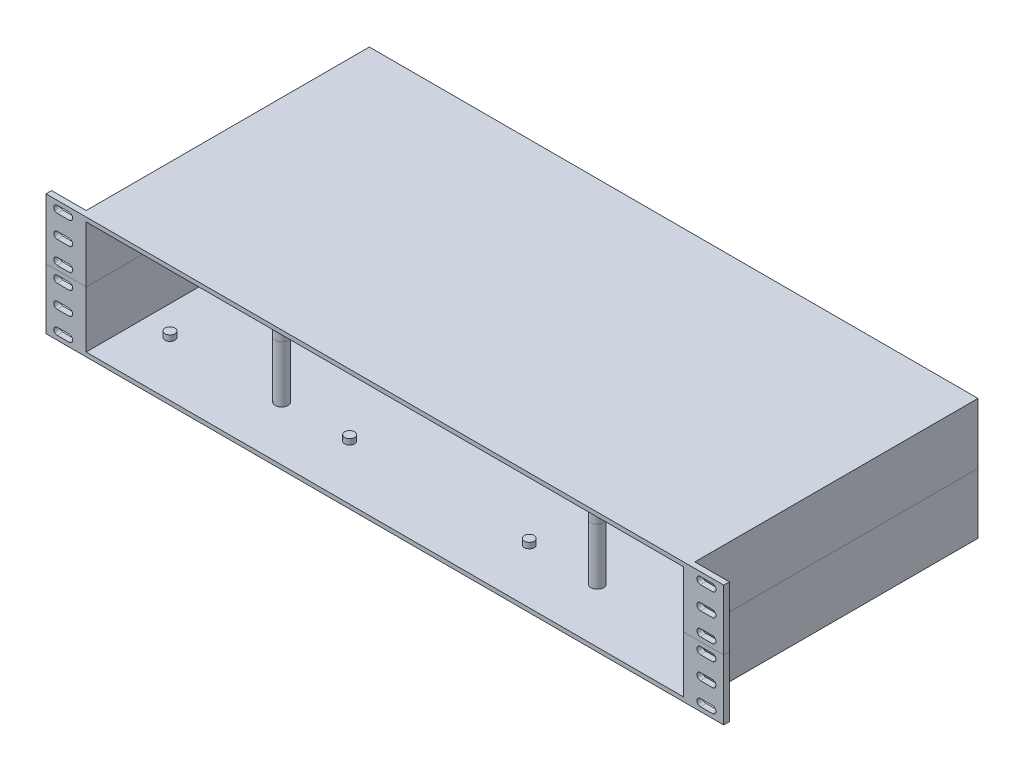
SolidWorks part; units mm, degrees
ref_plane "Front Plane" through (0, 0, 0) normal (0, 0, 1) x (1, 0, 0)
ref_plane "Top Plane" through (0, 0, 0) normal (0, 1, 0) x (1, 0, 0)
ref_plane "Right Plane" through (0, 0, 0) normal (1, 0, 0) x (0, 0, -1)
sketch "Sketch1" plane through (0, 0, 0) normal (0, 1, 0) x (1, 0, 0)
  line L0 (-15.8852, 0) -> (-227.8852, 0) construction
  line L1 (212, -98.3) -> (-212, -98.3)
  line L2 (212, -98.3) -> (212, 98.3)
  line L3 (212, 98.3) -> (-212, 98.3)
  line L4 (-212, -98.3) -> (-212, 98.3)
  line L5 (212, -98.3) -> (-212, 98.3) construction
  line L6 (212, 98.3) -> (-212, -98.3) construction
  line L7 (216, -102.5) -> (-216, -102.5)
  line L8 (216, -102.5) -> (216, 102.5)
  line L9 (216, 102.5) -> (-216, 102.5)
  line L10 (-216, -102.5) -> (-216, 102.5)
  line L11 (216, -102.5) -> (-216, 102.5) construction
  line L12 (216, 102.5) -> (-216, -102.5) construction
  line L13 (0, -98.3) -> (0, 98.3) construction
  point P0 (0, 0)
  point P6 (0, 0)
  point P14 (63.75, 63.75)
  point P16 (112, 63.75)
  point P17 (191.25, 63.75)
  dimension "D1" = 432
  dimension "D2" = 424
  dimension "D3" = 205
  dimension "D4" = 196.6
  dimension "D5" = 63.75
  dimension "D6" = 382.5
  dimension "D7" = 127.5
  dimension "D8" = 224
sketch "Sketch2" plane through (0, 0, 0) normal (0, 1, 0) x (1, 0, 0)
  line L0 (216, 102.5) -> (-216, 102.5) construction
  line L1 (216, -102.5) -> (216, 102.5) construction
  line L2 (216, -102.5) -> (-216, -102.5) construction
  line L3 (-216, -102.5) -> (-216, 102.5) construction
  line L4 (216, 102.5) -> (-216, 102.5)
  line L5 (216, -102.5) -> (216, 102.5)
  line L6 (216, -102.5) -> (-216, -102.5)
  line L7 (-216, -102.5) -> (-216, 102.5)
extrude "Boss-Extrude1" add sketch "Sketch2" along normal blind 3
sketch "Sketch3" plane through (0, 3, 0) normal (0, 1, 0) x (1, 0, 0)
  line L0 (216, -102.5) -> (-216, -102.5) construction
  line L1 (-212, -98.3) -> (-212, 98.3) construction
  line L2 (212, 98.3) -> (-212, 98.3) construction
  line L3 (212, -98.3) -> (212, 98.3) construction
  line L4 (216, -102.5) -> (216, 102.5) construction
  line L5 (216, 102.5) -> (-216, 102.5) construction
  line L6 (-216, -102.5) -> (-216, 102.5) construction
  line L7 (216, -102.5) -> (212, -102.5)
  line L8 (-212, -102.5) -> (-212, 98.3)
  line L9 (212, 98.3) -> (-212, 98.3)
  line L10 (212, -102.5) -> (212, 98.3)
  line L11 (216, -102.5) -> (216, 102.5)
  line L12 (216, 102.5) -> (-216, 102.5)
  line L13 (-216, -102.5) -> (-216, 102.5)
  line L14 (-212, -102.5) -> (-216, -102.5)
extrude "Boss-Extrude2" add sketch "Sketch3" along normal blind 40
sketch "Sketch4" plane through (0, 3, 0) normal (0, 1, 0) x (1, 0, 0)
  circle A0 centre (63.75, 63.75) radius 3.5
  circle A1 centre (191.25, 63.75) radius 3.5
  dimension "D1" = 7
extrude "Boss-Extrude3" add sketch "Sketch4" along normal blind 4
sketch "Sketch5" plane through (0, 3, 0) normal (0, 1, 0) x (1, 0, 0)
  circle A0 centre (112, 63.75) radius 4.5
  dimension "D1" = 9
extrude "Boss-Extrude4" add sketch "Sketch5" along normal blind 40
sketch "Sketch6" plane through (0, 0, 102.5) normal (0, 0, 1) x (1, 0, 0)
  line L0 (-216, 0) -> (216, 0) construction
  line L1 (216, 43) -> (240.5, 43)
  line L2 (216, 43) -> (216, 0)
  line L3 (216, 0) -> (240.5, 0)
  line L4 (240.5, 43) -> (240.5, 0)
  line L5 (0, 0) -> (0, 43) construction
  line L6 (-212, 43) -> (212, 43) construction
  line L7 (216, 21.5) -> (240.5, 21.5) construction
  line L8 (224, 21.5) -> (232.5, 21.5) construction
  line L9 (224, 24) -> (232.5, 24)
  line L10 (224, 19) -> (232.5, 19)
  line L11 (228.25, 43) -> (228.25, 21.5) construction
  line L12 (224, 37.5) -> (232.5, 37.5) construction
  line L13 (224, 40) -> (232.5, 40)
  line L14 (224, 35) -> (232.5, 35)
  line L15 (224, 5.5) -> (232.5, 5.5) construction
  line L16 (224, 8) -> (232.5, 8)
  line L17 (224, 3) -> (232.5, 3)
  arc A0 (224, 24) -> (224, 19) centre (224, 21.5) ccw
  arc A1 (232.5, 19) -> (232.5, 24) centre (232.5, 21.5) ccw
  arc A2 (224, 40) -> (224, 35) centre (224, 37.5) ccw
  arc A3 (232.5, 35) -> (232.5, 40) centre (232.5, 37.5) ccw
  arc A4 (224, 8) -> (224, 3) centre (224, 5.5) ccw
  arc A5 (232.5, 3) -> (232.5, 8) centre (232.5, 5.5) ccw
  point P16 (228.25, 21.5)
  point P26 (228.25, 37.5)
  point P33 (228.25, 5.5)
  dimension "D2" = 2.5
  dimension "D1" = 481
  dimension "D3" = 465
  dimension "D4" = 2
  dimension "D5" = 2
extrude "Boss-Extrude5" add sketch "Sketch6" against normal blind 4
mirror "Mirror3" about plane through (0, 0, 0) normal (1, 0, 0) of "Boss-Extrude5"
mirror "Mirror4" about plane through (0, 0, 0) normal (1, 0, 0) of "Boss-Extrude3", "Boss-Extrude4"
mirror "Mirror5" about plane through (0, 0, 0) normal (0, 0, 1) of "Mirror4", "Boss-Extrude3", "Boss-Extrude4"
mirror "Mirror6" about plane through (0, 43, 0) normal (0, 1, 0) of bodies 108
sketch "Sketch7" plane through (0, 3, 0) normal (0, 1, 0) x (1, 0, 0)
  line L1 (45.1085, 80.5902) -> (211.4317, 80.5902)
  line L2 (45.1085, 80.5902) -> (45.1085, 43.1458)
  line L3 (45.1085, 43.1458) -> (211.4317, 43.1458)
  line L4 (211.4317, 80.5902) -> (211.4317, 43.1458)
extrude "Cut-Extrude1" cut sketch "Sketch7" along normal offset from surface (62 mm away) 18 up to face at (112, 83, 68.25)
